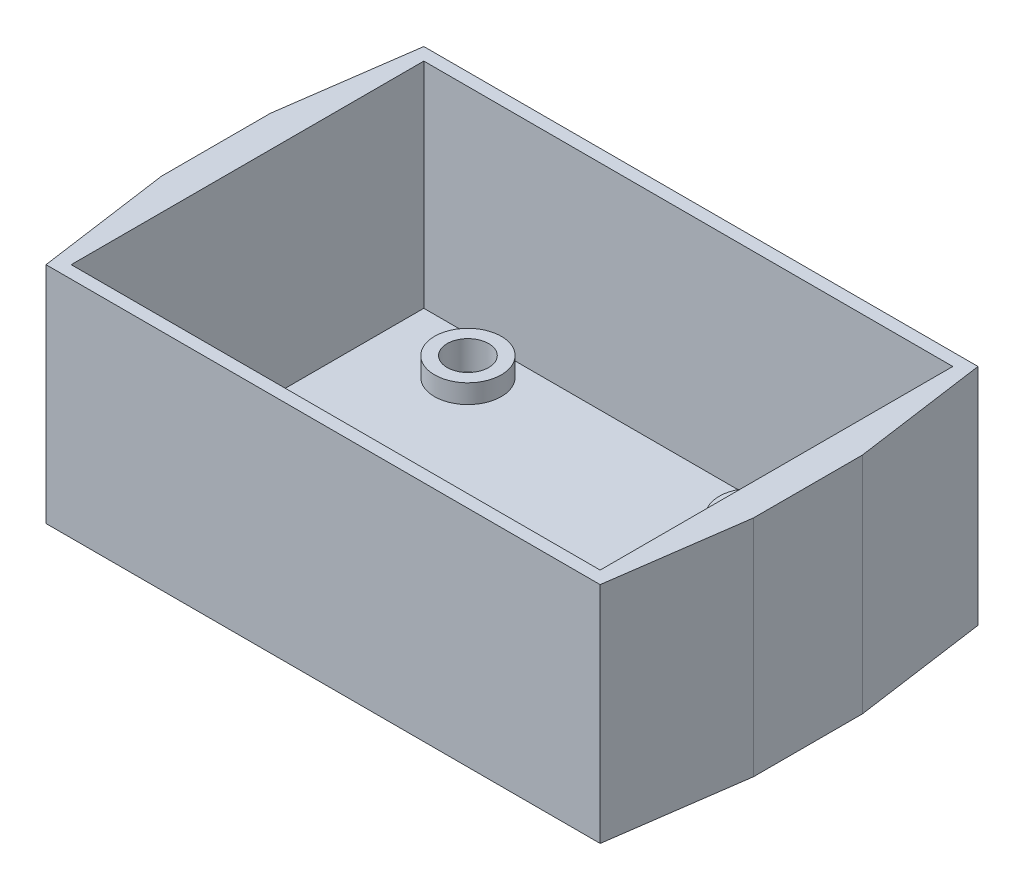
SolidWorks part; units mm, degrees
ref_plane "Front Plane" through (0, 0, 0) normal (0, 0, 1) x (1, 0, 0)
ref_plane "Top Plane" through (0, 0, 0) normal (0, 1, 0) x (1, 0, 0)
ref_plane "Right Plane" through (0, 0, 0) normal (1, 0, 0) x (0, 0, -1)
sketch "Sketch1" plane through (0, 0, 0) normal (0, 1, 0) x (1, 0, 0)
  line L0 (-22, 15) -> (-23.5, 4.3269)
  line L1 (-21, 14) -> (21, 14)
  line L2 (-21, 14) -> (-21, -14)
  line L3 (-21, -14) -> (21, -14)
  line L4 (21, 14) -> (21, -14)
  line L5 (-21, 14) -> (21, -14) construction
  line L6 (-21, -14) -> (21, 14) construction
  line L7 (-22, 15) -> (22, 15)
  line L9 (-22, -15) -> (22, -15)
  line L11 (-22, 15) -> (22, -15) construction
  line L12 (-22, -15) -> (22, 15) construction
  line L13 (-23.5, 4.3269) -> (-23.5, -4.3269)
  line L14 (-23.5, -4.3269) -> (-22, -15)
  line L15 (22, 15) -> (23.5, 4.3269)
  line L16 (23.5, 4.3269) -> (23.5, -4.3269)
  line L17 (23.5, -4.3269) -> (22, -15)
  point P0 (0, 0)
  point P6 (0, 0)
  dimension "D1" = 42
  dimension "D2" = 28
  dimension "D3" = 1
  dimension "D4" = 1
extrude "Boss-Extrude1" add sketch "Sketch1" along normal blind 17
sketch "Sketch3" plane through (0, 0, 0) normal (0, -1, 0) x (1, 0, 0)
  line L0 (-22, 15) -> (22, 15)
  line L1 (22, 15) -> (23.5, 4.3269)
  line L2 (23.5, 4.3269) -> (23.5, -4.3269)
  line L3 (23.5, -4.3269) -> (22, -15)
  line L4 (22, -15) -> (-22, -15)
  line L5 (-22, -15) -> (-23.5, -4.3269)
  line L6 (-23.5, -4.3269) -> (-23.5, 4.3269)
  line L7 (-23.5, 4.3269) -> (-22, 15)
extrude "Boss-Extrude3" add sketch "Sketch3" along normal blind 0.8
sketch "Sketch4" plane through (0, 0, 0) normal (0, 1, 0) x (1, 0, 0)
  line L0 (-21, 14) -> (-21, -14) construction
  line L1 (-21, 14) -> (-21, -14) construction
  line L2 (21, 14) -> (-21, 14) construction
  line L3 (-21, -14) -> (21, -14) construction
  line L4 (21, -14) -> (21, 14) construction
  circle A0 centre (-14.5, 11) radius 1.65
  circle A1 centre (7.8, 11.3028) radius 1.65
  circle A2 centre (-14.5, -11) radius 1.65
  circle A3 centre (7.8, -11.1651) radius 1.65
  dimension "D1" = 3.3
  dimension "D2" = 3.3
  dimension "D3" = 3.3
  dimension "D4" = 3.3
  dimension "D5" = 6.5
  dimension "D6" = 6.5
  dimension "D7" = 3
  dimension "D8" = 3
  dimension "D9" = 13.2
  dimension "D10" = 13.2
extrude "Cut-Extrude1" cut sketch "Sketch4" against normal blind 10.8
sketch "Sketch5" plane through (0, 0, -14) normal (0, 0, 1) x (1, 0, 0)
  line L0 (21, 17) -> (21, 0) construction
  line L1 (21, 1.5) -> (11, 1.5)
  line L2 (21, 1.5) -> (21, 6.5)
  line L3 (21, 6.5) -> (11, 6.5)
  line L4 (11, 1.5) -> (11, 6.5)
  line L5 (21, 0) -> (-21, 0) construction
  dimension "D1" = 1.5
  dimension "D2" = 10
  dimension "D3" = 5
extrude "Cut-Extrude2" cut sketch "Sketch5" against normal blind 10.8
fillet "Fillet1" radius 1.5 2 edges at (11, 1.5, -14.5) (11, 6.5, -14.5)
sketch "Sketch6" plane through (0, 0, 0) normal (0, 1, 0) x (1, 0, 0)
  circle A0 centre (-14.5, 11) radius 2.65
  circle A1 centre (7.8, 11.3028) radius 2.65
  circle A2 centre (7.8, -11.1651) radius 2.65
  circle A3 centre (-14.5, -11) radius 2.65
  circle A4 centre (-14.5, 11) radius 1.65 construction
  circle A5 centre (7.8, 11.3028) radius 1.65 construction
  circle A6 centre (7.8, -11.1651) radius 1.65 construction
  circle A7 centre (-14.5, -11) radius 1.65 construction
  circle A8 centre (-14.5, 11) radius 1.65
  circle A9 centre (7.8, 11.3028) radius 1.65
  circle A10 centre (7.8, -11.1651) radius 1.65
  circle A11 centre (-14.5, -11) radius 1.65
  dimension "D1" = 1
  dimension "D2" = 1
  dimension "D3" = 1
  dimension "D4" = 1
extrude "Boss-Extrude4" add sketch "Sketch6" along normal blind 1.5
